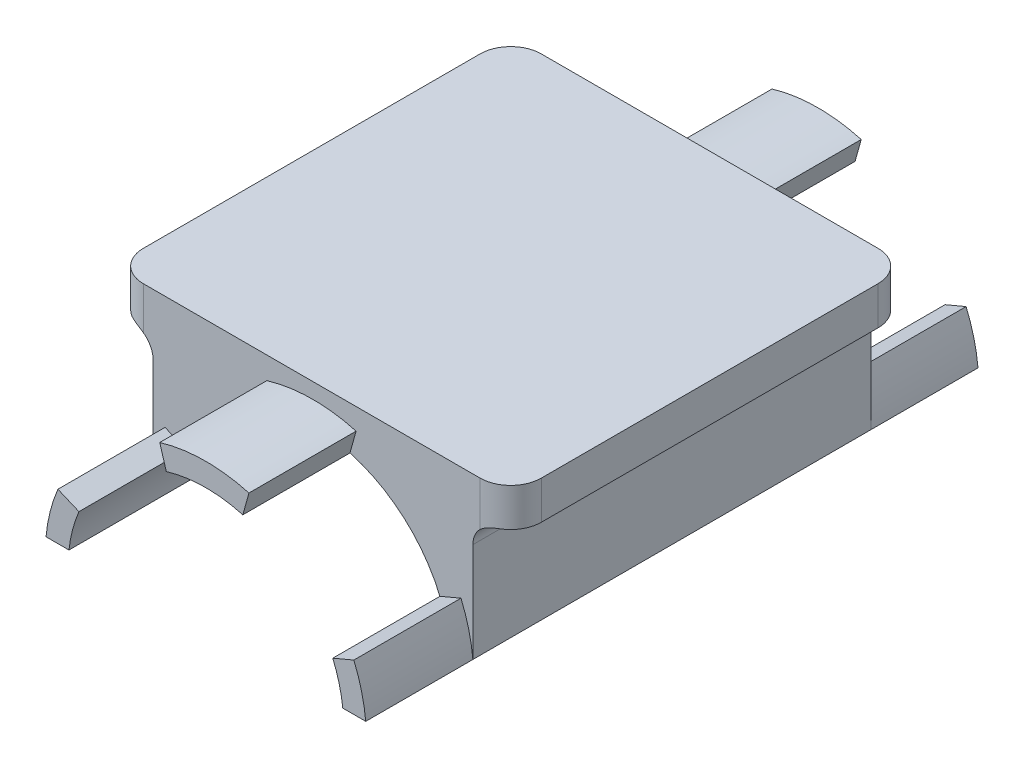
SolidWorks part; units mm, degrees
ref_plane "Front Plane" through (0, 0, 0) normal (0, 0, 1) x (1, 0, 0)
ref_plane "Top Plane" through (0, 0, 0) normal (0, 1, 0) x (1, 0, 0)
ref_plane "Right Plane" through (0, 0, 0) normal (1, 0, 0) x (0, 0, -1)
sketch "Sketch1" plane through (0, 0, 0) normal (0, 1, 0) x (1, 0, 0)
  line L1 (-13, -13) -> (13, -13)
  line L2 (-13, -13) -> (-13, 13)
  line L3 (-13, 13) -> (13, 13)
  line L4 (13, -13) -> (13, 13)
  line L5 (-13, -13) -> (13, 13) construction
  line L6 (-13, 13) -> (13, -13) construction
  point P0 (0, 0)
  dimension "D1" = 26
  dimension "D2" = 26
extrude "Boss-Extrude1" add sketch "Sketch1" along normal blind 2.5
sketch "Sketch2" plane through (0, 0, 0) normal (0, 0, 1) x (1, 0, 0)
  line L1 (10.5294, 0) -> (-10.3592, 0)
  line L2 (10.5294, 0) -> (10.5294, -8)
  line L3 (10.5294, -8) -> (-10.3592, -8)
  line L4 (-10.3592, 0) -> (-10.3592, -8)
  arc A0 (9.0294, -8) -> (-8.8592, -8) centre (0.0851, -8.9996) ccw
  dimension "D2" = 1.5
  dimension "D1" = 8
  dimension "D3" = 1.5
extrude "Boss-Extrude2" add sketch "Sketch2" along normal up to surface and the other way up to surface contours A0 L3 L2 L1 | A0 L1 L4 L3 up to face at (0, 1.25, 13) other way up to face at (0, 1.25, -13)
sketch "Sketch3" plane through (0, 0, 0) normal (0, 0, 1) x (1, 0, 0)
  line L0 (0.0851, -8.9996) -> (2.5, -0.3296)
  line L1 (2.5, -0.3296) -> (2.9004, 1.1077)
  line L2 (0.0851, -8.9996) -> (-2.5, -0.3788)
  line L3 (-2.5, -0.3788) -> (-2.9286, 1.0503)
  line L4 (-10.3592, -8) -> (-8.8592, -8)
  line L5 (0.0851, -8.9996) -> (-8.2067, -5.5)
  line L6 (-8.2067, -5.5) -> (-9.5813, -4.9198)
  line L7 (-9.5813, -4.9198) -> (-9.5957, -4.9369)
  line L8 (0.0851, -8.9996) -> (8.3768, -5.5)
  line L9 (8.3768, -5.5) -> (9.7514, -4.9198)
  line L10 (9.0294, -8) -> (10.5294, -8)
  circle A0 centre (0.0851, -8.9996) radius 10.492
  arc A1 (-8.8592, -8) -> (9.0294, -8) centre (0.0851, -8.9996) cw
  dimension "D1" = 2.5
  dimension "D2" = 2.5
  dimension "D3" = 2.5
  dimension "D4" = 2.5
extrude "Boss-Extrude3" add sketch "Sketch3" along normal offset from surface 7 and the other way offset from surface (20 mm away) 7 contours L4 A1 L6 A0 | L9 A1 L10 A0 | L3 A1 L1 A0 up to face at (0.0567, -1.97, 13) offset beyond the face yes other way up to face at (0.0567, -1.97, -13)
fillet "Fillet1" radius 2 4 edges at (-13, 1.25, 13) (-13, 1.25, -13) (13, 1.25, -13) (13, 1.25, 13)
fillet "Fillet2" radius 1.5 2 edges at (-10.3592, 0, 0) (10.5294, 0, 0)
